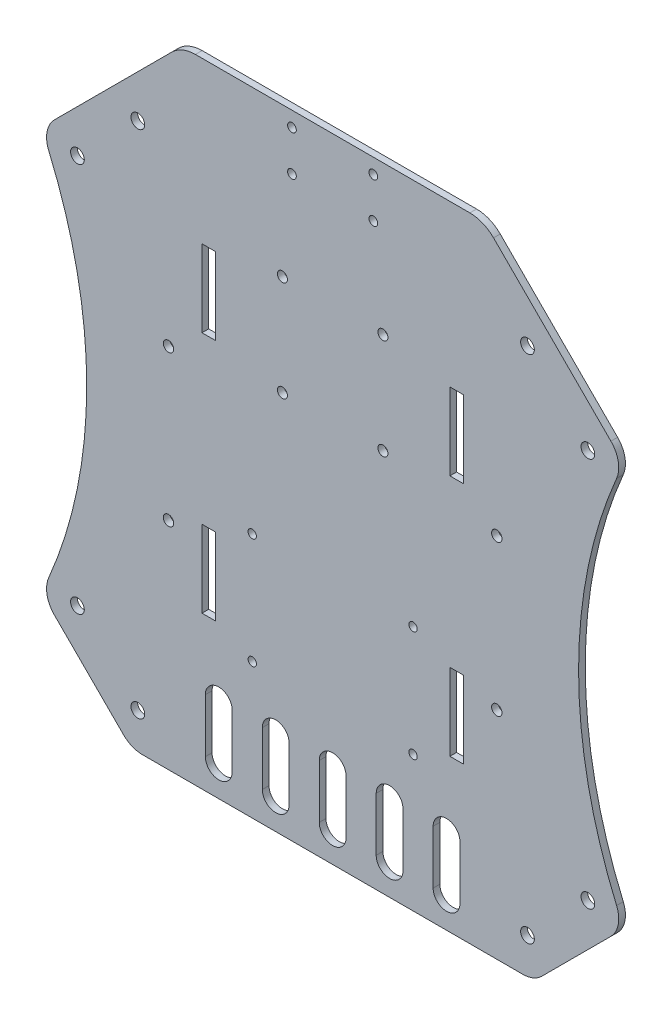
SolidWorks part; units mm, degrees
material "cf"
ref_plane "Front Plane" through (0, 0, 0) normal (0, 0, 1) x (1, 0, 0)
ref_plane "Top Plane" through (0, 0, 0) normal (0, 1, 0) x (1, 0, 0)
ref_plane "Right Plane" through (0, 0, 0) normal (1, 0, 0) x (0, 0, -1)
sketch "Sketch1" plane through (0, 0, 0) normal (0, 0, 1) x (1, 0, 0)
  line L0 (-82.7315, 60.1041) -> (-60.1041, 82.7315)
  line L5 (-27.5, -50) -> (27.5, -50) construction
  line L6 (-27.5, -50) -> (-27.5, -10) construction
  line L7 (-259.08, 259.08) -> (259.08, 259.08)
  line L8 (-259.08, 259.08) -> (-259.08, -259.08)
  line L9 (-259.08, -259.08) -> (259.08, -259.08)
  line L10 (259.08, 259.08) -> (259.08, -259.08)
  line L11 (-259.08, 259.08) -> (259.08, -259.08) construction
  line L12 (-259.08, -259.08) -> (259.08, 259.08) construction
  line L13 (-27.5, -10) -> (27.5, -10) construction
  line L14 (27.5, -50) -> (27.5, -10) construction
  line L15 (-27.5, -50) -> (27.5, -10) construction
  line L16 (-27.5, -10) -> (27.5, -50) construction
  line L17 (-17.5, 60) -> (17.5, 60) construction
  line L18 (-17.5, 60) -> (-17.5, 25) construction
  line L19 (-17.5, 25) -> (17.5, 25) construction
  line L20 (17.5, 60) -> (17.5, 25) construction
  line L21 (-76.1908, 58.1595) -> (-58.1595, 76.1908) construction
  line L22 (-39, 54) -> (-35, 54)
  line L23 (-82.7315, 60.1041) -> (-74.2462, 51.6188)
  line L24 (-60.1041, 82.7315) -> (-51.6188, 74.2462)
  line L25 (-74.2462, 51.6188) -> (-51.6188, 74.2462)
  line L26 (-82.7315, 60.1041) -> (-51.6188, 74.2462) construction
  line L27 (-60.1041, 82.7315) -> (-74.2462, 51.6188) construction
  line L28 (82.7315, -60.1041) -> (74.2462, -51.6188)
  line L29 (51.6188, -74.2462) -> (74.2462, -51.6188)
  line L30 (60.1041, -82.7315) -> (51.6188, -74.2462)
  line L31 (60.1041, -82.7315) -> (82.7315, -60.1041)
  line L32 (0, 0) -> (50000, 0) construction
  line L33 (60.1041, 82.7315) -> (82.7315, 60.1041)
  line L34 (60.1041, 82.7315) -> (51.6188, 74.2462)
  line L35 (51.6188, 74.2462) -> (74.2462, 51.6188)
  line L36 (82.7315, 60.1041) -> (74.2462, 51.6188)
  line L37 (-60.1041, -82.7315) -> (-51.6188, -74.2462)
  line L38 (-74.2462, -51.6188) -> (-51.6188, -74.2462)
  line L39 (-82.7315, -60.1041) -> (-74.2462, -51.6188)
  line L40 (-82.7315, -60.1041) -> (-60.1041, -82.7315)
  line L41 (-60.1041, 86.9741) -> (-47.3762, 74.2462)
  line L42 (-74.2462, 47.3762) -> (-47.3762, 74.2462)
  line L43 (-86.9741, 60.1041) -> (-74.2462, 47.3762)
  line L44 (-86.9741, 60.1041) -> (-60.1041, 86.9741)
  line L45 (60.1041, -86.9741) -> (86.9741, -60.1041)
  line L46 (60.1041, -86.9741) -> (47.3762, -74.2462)
  line L47 (47.3762, -74.2462) -> (74.2462, -47.3762)
  line L48 (86.9741, -60.1041) -> (74.2462, -47.3762)
  line L49 (60.1041, 86.9741) -> (47.3762, 74.2462)
  line L50 (47.3762, 74.2462) -> (74.2462, 47.3762)
  line L51 (86.9741, 60.1041) -> (74.2462, 47.3762)
  line L52 (60.1041, 86.9741) -> (86.9741, 60.1041)
  line L53 (-86.9741, -60.1041) -> (-60.1041, -86.9741)
  line L54 (-86.9741, -60.1041) -> (-74.2462, -47.3762)
  line L55 (-74.2462, -47.3762) -> (-47.3762, -74.2462)
  line L56 (-60.1041, -86.9741) -> (-47.3762, -74.2462)
  line L57 (0, 0) -> (0, 50000) construction
  line L58 (-60.1041, 86.9741) -> (60.1041, 86.9741)
  line L59 (-60.1041, -86.9741) -> (60.1041, -86.9741)
  line L60 (-39, 54) -> (-39, 31)
  line L61 (-30, -85) -> (30, -85)
  line L62 (-30, -85) -> (-30, 85)
  line L63 (-30, 85) -> (30, 85)
  line L64 (30, -85) -> (30, 85)
  line L65 (-30, -85) -> (30, 85) construction
  line L66 (-30, 85) -> (30, -85) construction
  line L67 (-55, -31.5) -> (55, -31.5) construction
  line L68 (-55, -31.5) -> (-55, 31.5) construction
  line L69 (-55, 31.5) -> (55, 31.5) construction
  line L70 (55, -31.5) -> (55, 31.5) construction
  line L71 (-55, -31.5) -> (55, 31.5) construction
  line L72 (-55, 31.5) -> (55, -31.5) construction
  line L73 (-39, 31) -> (-35, 31)
  line L74 (-35, 54) -> (-35, 31)
  line L75 (-39, 54) -> (-35, 31) construction
  line L76 (-39, 31) -> (-35, 54) construction
  line L77 (35, 54) -> (39, 54)
  line L78 (35, 54) -> (35, 31)
  line L79 (35, 31) -> (39, 31)
  line L80 (39, 54) -> (39, 31)
  line L81 (35, 54) -> (39, 31) construction
  line L82 (35, 31) -> (39, 54) construction
  line L83 (35, -18.5) -> (39, -18.5)
  line L84 (35, -18.5) -> (35, -41.5)
  line L85 (35, -41.5) -> (39, -41.5)
  line L86 (39, -18.5) -> (39, -41.5)
  line L87 (35, -18.5) -> (39, -41.5) construction
  line L88 (35, -41.5) -> (39, -18.5) construction
  line L89 (-39, -18.5) -> (-35, -18.5)
  line L90 (-39, -18.5) -> (-39, -41.5)
  line L91 (-39, -41.5) -> (-35, -41.5)
  line L92 (-35, -18.5) -> (-35, -41.5)
  line L93 (-39, -18.5) -> (-35, -41.5) construction
  line L94 (-39, -41.5) -> (-35, -18.5) construction
  line L95 (-78.4889, -55.8614) -> (-55.8614, -78.4889) construction
  arc A0 (-86.9741, -60.1041) -> (-86.9741, 60.1041) centre (-213.4158, 0) ccw
  arc A1 (86.9741, -60.1041) -> (86.9741, 60.1041) centre (213.4158, 0) cw
  circle A2 centre (-15, 57.5) radius 1.5
  circle A3 centre (-15, 27.5) radius 1.5
  circle A4 centre (15, 27.5) radius 1.5
  circle A5 centre (15, 57.5) radius 1.5
  circle A6 centre (-24, -13.5) radius 1.25
  circle A7 centre (24, -13.5) radius 1.25
  circle A8 centre (24, -46.5) radius 1.25
  circle A9 centre (-24, -46.5) radius 1.25
  circle A10 centre (-76.1908, 58.1595) radius 2.05
  circle A11 centre (-58.1595, 76.1908) radius 2.05
  circle A12 centre (76.1908, -58.1595) radius 2.05
  circle A13 centre (58.1595, -76.1908) radius 2.05
  circle A14 centre (-58.1595, -76.1908) radius 2.05
  circle A15 centre (-76.1908, -58.1595) radius 2.05
  circle A16 centre (58.1595, 76.1908) radius 2.05
  circle A17 centre (76.1908, 58.1595) radius 2.05
  circle A18 centre (-167.1561, -167.1561) radius 101.6 construction
  circle A19 centre (167.1561, 167.1561) radius 101.6 construction
  circle A20 centre (-167.1561, -167.1561) radius 114.3 construction
  circle A21 centre (-167.1561, -167.1561) radius 127 construction
  point P0 (0, 0)
  point P1 (0, -30)
  point P17 (-67.1751, 67.1751)
  point P48 (-60.8112, 60.8112)
  point P63 (0, 0)
  point P69 (0, 0)
  point P90 (37, 42.5)
  point P97 (-37, 42.5)
  point P102 (37, -30)
  point P107 (-37, -30)
  point P109 (-17.5, 42.5)
  dimension "D12" = 140
  dimension "D18" = 3
  dimension "D24" = 2.5
  dimension "D36" = 4.1
  dimension "D42" = 203.2
  dimension "D43" = 472.7889
  dimension "D45" = 228.6
  dimension "D46" = 254
  dimension "D1" = 35
  dimension "D2" = 35
  dimension "D3" = 55
  dimension "D4" = 40
  dimension "D5" = 10
  dimension "D6" = 25
  dimension "D7" = 32
  dimension "D8" = 12
  dimension "D9" = 518.16
  dimension "D10" = 95
  dimension "D13" = 25.5
  dimension "D14" = 170
  dimension "D15" = 60
  dimension "D16" = 110
  dimension "D17" = 63
  dimension "D19" = 2.5
  dimension "D20" = 2.5
  dimension "D21" = 30
  dimension "D22" = 2.5
  dimension "D23" = 2.5
  dimension "D25" = 3.5
  dimension "D26" = 3.5
  dimension "D27" = 3.5
  dimension "D28" = 3.5
  dimension "D29" = 23
  dimension "D30" = 4
  dimension "D31" = 5
  dimension "D32" = 5
  dimension "D33" = 5
  dimension "D34" = 5
  dimension "D35" = 12.75
  dimension "D37" = 280.3944
  dimension "D38" = 17.5
  dimension "D39" = 30
  dimension "D40" = 130
  dimension "D41" = 130
  dimension "D44" = 236.3944
  dimension "D11" = 3
extrude "Boss-Extrude1" add sketch "Sketch1" along normal blind 2 contours L48 A1 L51 L50 L49 L58 L41 L42 L43 A0 L54 L55 L56 L59 L46 L47 L64 L61 L62 L63 | L53 L56 L55 L54 L40 L39 L38 L37 | L39 L40 L37 L38 | L30 L31 L28 L29 | L45 L48 L47 L46 L31 L30 L29 L28 | L52 L49 L50 L51 L33 L36 L35 L34 | L36 L33 L34 L35 | L44 L43 L42 L41 L25 L23 L0 L24 | L23 L25 L24 L0 | L61 L64 L63 L62
fillet "Fillet7" radius 8 8 edges at (86.9741, -60.1041, 1) (60.1041, -86.9741, 1) (-60.1041, -86.9741, 1) (-86.9741, -60.1041, 1) (-60.1041, 86.9741, 1) (60.1041, 86.9741, 1) (86.9741, 60.1041, 1) (-86.9741, 60.1041, 1)
sketch "Sketch2" plane through (0, 0, 2) normal (0, 0, 1) x (1, 0, 0)
  line L0 (-62.4472, 84.631) -> (-45.1041, 101.9741)
  line L1 (-45.1041, 101.9741) -> (45.1041, 101.9741)
  line L2 (0, 0) -> (0, 118.5934) construction
  line L3 (62.4472, 84.631) -> (45.1041, 101.9741)
  line L4 (62.4472, 84.631) -> (83.0638, 64.0144) construction
  line L5 (-56.7904, 86.9741) -> (56.7904, 86.9741) construction
  line L7 (-56.7904, 86.9741) -> (56.7904, 86.9741)
  arc A1 (62.4472, 84.631) -> (56.7904, 86.9741) centre (56.7904, 78.9741) ccw construction
  arc A2 (-56.7904, 86.9741) -> (-62.4472, 84.631) centre (-56.7904, 78.9741) ccw construction
  arc A3 (62.4472, 84.631) -> (56.7904, 86.9741) centre (56.7904, 78.9741) ccw
  arc A4 (-56.7904, 86.9741) -> (-62.4472, 84.631) centre (-56.7904, 78.9741) ccw
  dimension "D1" = 15
extrude "Boss-Extrude2" add sketch "Sketch2" against normal blind 2
fillet "Fillet8" radius 10 2 edges at (-45.1041, 101.9741, 1) (45.1041, 101.9741, 1)
sketch "Sketch5" plane through (0, 0, 2) normal (0, 0, 1) x (1, 0, 0)
  line L0 (49, 22.5) -> (49, -22.5) construction
  line L1 (49, 22.5) -> (71, 0)
  line L2 (71, 0) -> (49, -22.5)
  line L3 (0, 0) -> (0, 50000) construction
  line L4 (-49, 22.5) -> (-49, -22.5) construction
  line L5 (-71, 0) -> (-49, -22.5)
  line L6 (-49, 22.5) -> (-71, 0)
  circle A0 centre (49, 22.5) radius 1.55
  circle A1 centre (49, -22.5) radius 1.55
  circle A2 centre (-49, -22.5) radius 1.55
  circle A3 centre (-49, 22.5) radius 1.55
  point P4 (49, 0)
  dimension "D1" = 3.1
  dimension "D2" = 45
  dimension "D3" = 22
  dimension "D4" = 49
extrude "Cut-Extrude1" cut sketch "Sketch5" against normal blind 10
sketch "Sketch6" plane through (0, 0, 2) normal (0, 0, 1) x (1, 0, 0)
  line L0 (-34, -62.0741) -> (-34, -78.0741) construction
  line L1 (-30, -62.0741) -> (-30, -78.0741)
  line L2 (-38, -62.0741) -> (-38, -78.0741)
  line L3 (-17, -62.0741) -> (-17, -78.0741) construction
  line L4 (-13, -62.0741) -> (-13, -78.0741)
  line L5 (-21, -62.0741) -> (-21, -78.0741)
  line L6 (0, -62.0741) -> (0, -78.0741) construction
  line L7 (4, -62.0741) -> (4, -78.0741)
  line L8 (-4, -62.0741) -> (-4, -78.0741)
  line L9 (17, -62.0741) -> (17, -78.0741) construction
  line L10 (21, -62.0741) -> (21, -78.0741)
  line L11 (13, -62.0741) -> (13, -78.0741)
  line L12 (34, -62.0741) -> (34, -78.0741) construction
  line L13 (38, -62.0741) -> (38, -78.0741)
  line L14 (30, -62.0741) -> (30, -78.0741)
  line L15 (-56.7904, -86.9741) -> (56.7904, -86.9741) construction
  arc A0 (-30, -62.0741) -> (-38, -62.0741) centre (-34, -62.0741) ccw
  arc A1 (-38, -78.0741) -> (-30, -78.0741) centre (-34, -78.0741) ccw
  arc A2 (-13, -62.0741) -> (-21, -62.0741) centre (-17, -62.0741) ccw
  arc A3 (-21, -78.0741) -> (-13, -78.0741) centre (-17, -78.0741) ccw
  arc A4 (4, -62.0741) -> (-4, -62.0741) centre (0, -62.0741) ccw
  arc A5 (-4, -78.0741) -> (4, -78.0741) centre (0, -78.0741) ccw
  arc A6 (21, -62.0741) -> (13, -62.0741) centre (17, -62.0741) ccw
  arc A7 (13, -78.0741) -> (21, -78.0741) centre (17, -78.0741) ccw
  arc A8 (38, -62.0741) -> (30, -62.0741) centre (34, -62.0741) ccw
  arc A9 (30, -78.0741) -> (38, -78.0741) centre (34, -78.0741) ccw
  point P2 (-34, -70.0741)
  point P7 (-17, -70.0741)
  point P14 (0, -70.0741)
  point P21 (17, -70.0741)
  point P29 (34, -70.0741)
  dimension "D6" = 4
  dimension "D1" = 16
  dimension "D2" = 17
  dimension "D3" = 17
  dimension "D4" = 17
  dimension "D5" = 17
  dimension "D7" = 8.9
extrude "Cut-Extrude2" cut sketch "Sketch6" against normal blind 10
sketch "Sketch7" plane through (0, 0, 2) normal (0, 0, 1) x (1, 0, 0)
  line L0 (40.9619, 101.9741) -> (-40.9619, 101.9741) construction
  line L1 (-25, 74.9741) -> (-15, 74.9741) construction
  line L2 (-25, 76.9741) -> (-15, 76.9741)
  line L3 (-25, 72.9741) -> (-15, 72.9741)
  line L4 (15, 74.9741) -> (25, 74.9741) construction
  line L5 (15, 76.9741) -> (25, 76.9741)
  line L6 (15, 72.9741) -> (25, 72.9741)
  line L7 (-20, 74.9741) -> (20, 74.9741) construction
  circle A0 centre (0, 91.9741) radius 1.5
  arc A1 (-25, 76.9741) -> (-25, 72.9741) centre (-25, 74.9741) ccw
  arc A2 (-15, 72.9741) -> (-15, 76.9741) centre (-15, 74.9741) ccw
  arc A3 (15, 76.9741) -> (15, 72.9741) centre (15, 74.9741) ccw
  arc A4 (25, 72.9741) -> (25, 76.9741) centre (25, 74.9741) ccw
  point P7 (-20, 74.9741)
  point P12 (20, 74.9741)
  point P21 (0, 74.9741)
  point P22 (20, 84.9114)
  dimension "D2" = 3
  dimension "D7" = 2
  dimension "D1" = 10
  dimension "D3" = 10
  dimension "D4" = 40
  dimension "D5" = 27
  dimension "D6" = 10
extrude "Cut-Extrude3" [suppressed] cut sketch "Sketch7" against normal blind 10
sketch "Sketch8" plane through (0, 0, 2) normal (0, 0, 1) x (1, 0, 0)
  line L0 (40.9619, 101.9741) -> (-40.9619, 101.9741) construction
  line L1 (-12.15, 97.4741) -> (12.15, 97.4741) construction
  line L2 (-12.15, 97.4741) -> (-12.15, 85.4741) construction
  line L3 (-12.15, 85.4741) -> (12.15, 85.4741) construction
  line L4 (12.15, 97.4741) -> (12.15, 85.4741) construction
  line L5 (-12.15, 97.4741) -> (12.15, 85.4741) construction
  line L6 (-12.15, 85.4741) -> (12.15, 97.4741) construction
  circle A0 centre (12.15, 97.4741) radius 1.3
  circle A1 centre (12.15, 85.4741) radius 1.3
  circle A2 centre (-12.15, 85.4741) radius 1.3
  circle A3 centre (-12.15, 97.4741) radius 1.3
  point P0 (0, 91.4741)
  dimension "D2" = 2.6
  dimension "D1" = 12
  dimension "D3" = 24.3
  dimension "D4" = 4.5
extrude "Cut-Extrude4" cut sketch "Sketch8" against normal blind 10
